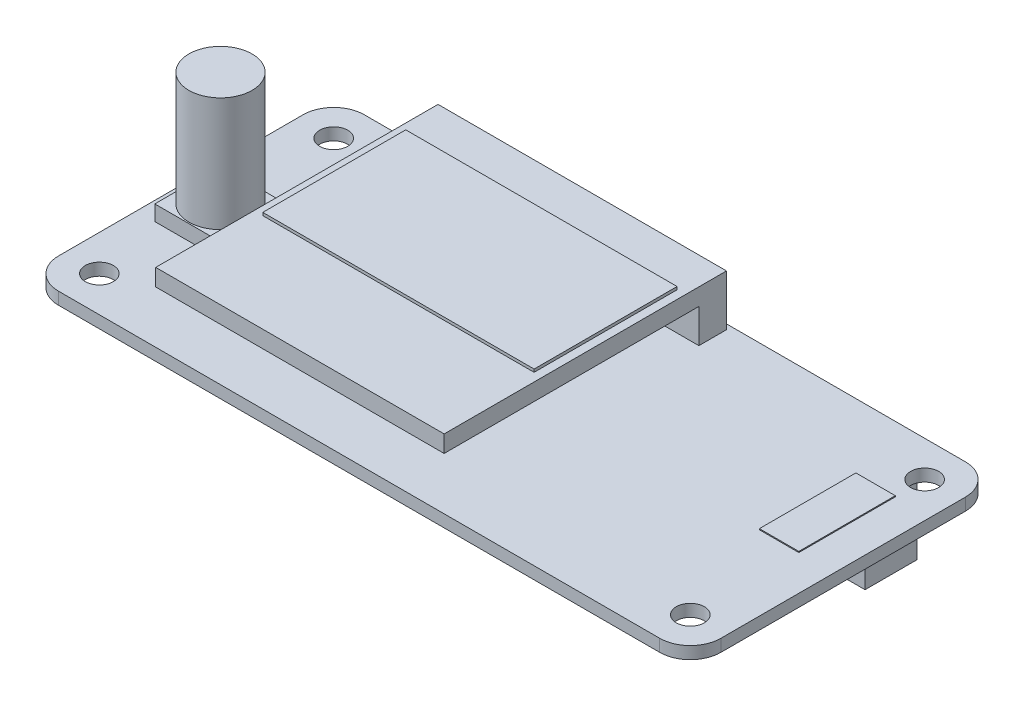
SolidWorks part; units mm, degrees
ref_plane "前视基准面" through (0, 0, 0) normal (0, 0, 1) x (1, 0, 0)
ref_plane "上视基准面" through (0, 0, 0) normal (0, 1, 0) x (1, 0, 0)
ref_plane "右视基准面" through (0, 0, 0) normal (1, 0, 0) x (0, 0, -1)
sketch "草图1" plane through (0, 0, 0) normal (0, 1, 0) x (1, 0, 0)
  line L1 (-29.5, 15) -> (29.5, 15)
  line L2 (-32.5, 12) -> (-32.5, -12)
  line L3 (-29.5, -15) -> (29.5, -15)
  line L4 (32.5, 12) -> (32.5, -12)
  line L5 (-32.5, 15) -> (32.5, -15) construction
  line L6 (-32.5, -15) -> (32.5, 15) construction
  arc A0 (29.5, 15) -> (32.5, 12) centre (29.5, 12) cw
  arc A1 (29.5, -15) -> (32.5, -12) centre (29.5, -12) ccw
  arc A2 (-32.5, -12) -> (-29.5, -15) centre (-29.5, -12) ccw
  arc A3 (-29.5, 15) -> (-32.5, 12) centre (-29.5, 12) ccw
  point P0 (0, 0)
  dimension "D3" = 3
  dimension "D1" = 65
  dimension "D2" = 30
extrude "凸台-拉伸1" add sketch "草图1" along normal blind 1.2
sketch "草图2" plane through (0, 1.2, 0) normal (0, 1, 0) x (1, 0, 0)
  line L0 (-29.5, -15) -> (29.5, -15) construction
  line L1 (32.5, -12) -> (32.5, 12) construction
  line L2 (29.5, 15) -> (-29.5, 15) construction
  circle A0 centre (29, -11.5) radius 1.375
  circle A1 centre (29, 11.5) radius 1.375
  circle A2 centre (-29, -11.5) radius 1.375
  circle A3 centre (-29, 11.5) radius 1.375
  dimension "D1" = 2.75
  dimension "D2" = 3.5
  dimension "D3" = 3.5
  dimension "D4" = 3.5
  dimension "D5" = 3.5
extrude "切除-拉伸1" cut sketch "草图2" against normal blind 1.2
sketch "草图11" plane through (0, 0, 0) normal (0, -1, 0) x (1, 0, 0)
  line L0 (29.5, -15) -> (-29.5, -15) construction
  line L1 (25.65, -14.1) -> (-25.75, -14.1)
  line L2 (25.65, -14.1) -> (25.65, -9)
  line L3 (25.65, -9) -> (-25.75, -9)
  line L4 (-25.75, -14.1) -> (-25.75, -9)
  line L5 (32.5, 12) -> (32.5, -12) construction
  dimension "D1" = 51.4
  dimension "D2" = 5.1
  dimension "D3" = 0.9
  dimension "D4" = 6.85
extrude "凸台-拉伸9" add sketch "草图11" along normal blind 8.6
sketch "草图12" plane through (0, 1.2, 0) normal (0, 1, 0) x (1, 0, 0)
  line L0 (29.5, 15) -> (-29.5, 15) construction
  line L1 (-30.7, 2.09) -> (-24.25, 2.09)
  line L2 (-30.7, 2.09) -> (-30.7, -4.36)
  line L3 (-30.7, -4.36) -> (-24.25, -4.36)
  line L4 (-24.25, 2.09) -> (-24.25, -4.36)
  line L5 (-30.7, 2.09) -> (-24.25, -4.36) construction
  line L6 (-30.7, -4.36) -> (-24.25, 2.09) construction
  line L7 (-32.5, 12) -> (-32.5, -12) construction
  point P0 (-27.475, -1.135)
  point P7 (0, 0)
  point P8 (-27.7945, -1.135)
  dimension "D1" = 6.45
  dimension "D2" = 6.45
  dimension "D3" = 12.91
  dimension "D4" = 1.8
extrude "凸台-拉伸10" add sketch "草图12" along normal blind 1.5
sketch "草图13" plane through (0, 2.7, 0) normal (0, 1, 0) x (1, 0, 0)
  circle A0 centre (-27.475, -1.135) radius 3.1
  dimension "D1" = 6.2
extrude "凸台-拉伸11" add sketch "草图13" along normal blind 11.2 contours A0
sketch "草图14" plane through (0, 1.2, 0) normal (0, 1, 0) x (1, 0, 0)
  line L0 (29.5, 15) -> (-29.5, 15) construction
  line L1 (-21.76, 14.5) -> (6.55, 14.5)
  line L2 (-21.76, 14.5) -> (-21.76, -13.21)
  line L3 (-21.76, -13.21) -> (6.55, -13.21)
  line L4 (6.55, 14.5) -> (6.55, -13.21)
  line L5 (-32.5, 12) -> (-32.5, -12) construction
  dimension "D1" = 28.31
  dimension "D2" = 27.71
  dimension "D3" = 0.5
  dimension "D4" = 10.74
extrude "凸台-拉伸12" add sketch "草图14" along normal blind 5
sketch "草图15" plane through (0, 6.2, 0) normal (0, 1, 0) x (1, 0, 0)
  line L0 (29.5, 15) -> (-29.5, 15) construction
  line L1 (-20.9, 10.47) -> (5.73, 10.47)
  line L2 (-20.9, 10.47) -> (-20.9, -3.56)
  line L3 (-20.9, -3.56) -> (5.73, -3.56)
  line L4 (5.73, 10.47) -> (5.73, -3.56)
  line L5 (-32.5, 12) -> (-32.5, -12) construction
  dimension "D1" = 26.63
  dimension "D2" = 14.03
  dimension "D3" = 4.53
  dimension "D4" = 11.6
extrude "凸台-拉伸13" add sketch "草图15" along normal blind 0.28
sketch "草图16" plane through (0, 1.2, 0) normal (0, 1, 0) x (1, 0, 0)
  line L0 (29.5, 15) -> (-29.5, 15) construction
  line L1 (25.17, 8.58) -> (29.04, 8.58)
  line L2 (25.17, 8.58) -> (25.17, -0.89)
  line L3 (25.17, -0.89) -> (29.04, -0.89)
  line L4 (29.04, 8.58) -> (29.04, -0.89)
  line L5 (32.5, -12) -> (32.5, 12) construction
  dimension "D1" = 9.47
  dimension "D2" = 3.87
  dimension "D3" = 6.42
  dimension "D4" = 3.46
extrude "凸台-拉伸14" add sketch "草图16" along normal blind 0.1
sketch "草图17" plane through (0, 0, 13.21) normal (0, 0, 1) x (1, 0, 0)
  line L0 (6.55, 6.2) -> (6.55, 1.2) construction
  line L1 (-21.76, 1.2) -> (6.55, 1.2)
  line L2 (-21.76, 1.2) -> (-21.76, 4.537)
  line L3 (-21.76, 4.537) -> (6.55, 4.537)
  line L4 (6.55, 1.2) -> (6.55, 4.537)
extrude "切除-拉伸2" cut sketch "草图17" against normal blind 25
